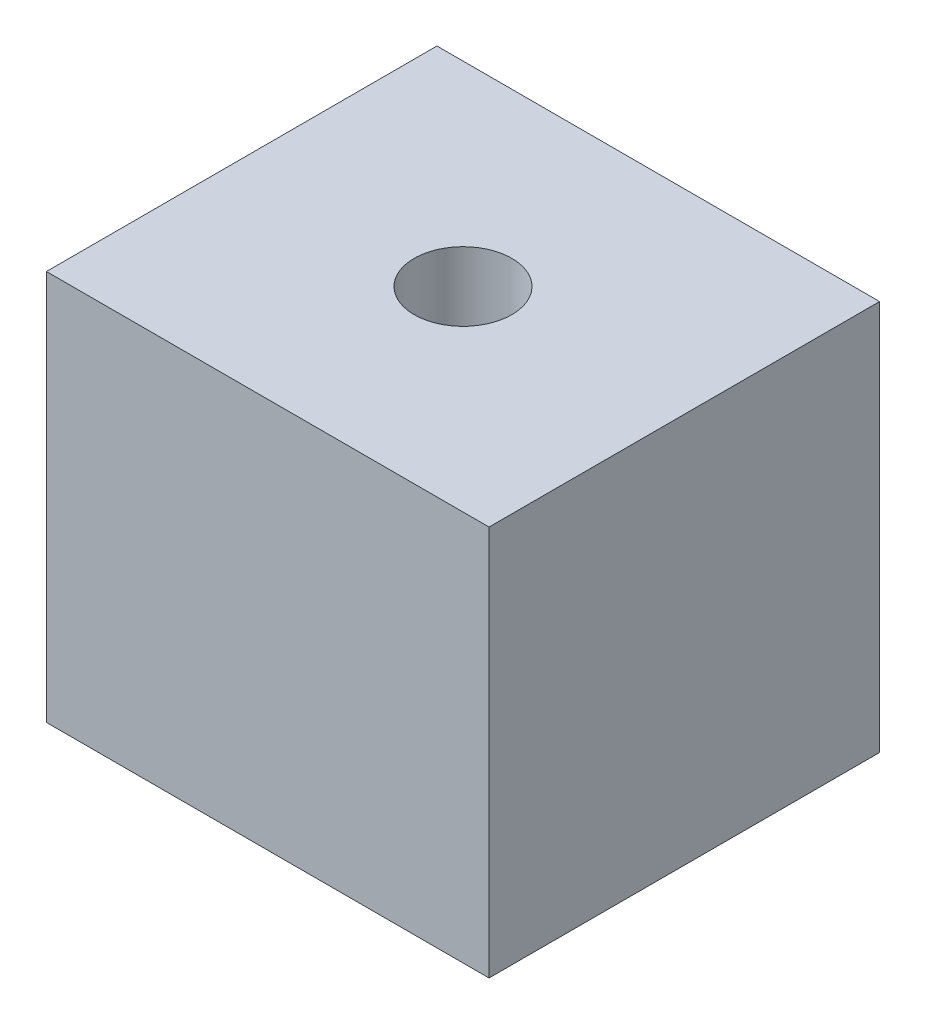
SolidWorks part; units mm, degrees
ref_plane "Front Plane" through (0, 0, 0) normal (0, 0, 1) x (1, 0, 0)
ref_plane "Top Plane" through (0, 0, 0) normal (0, 1, 0) x (1, 0, 0)
ref_plane "Right Plane" through (0, 0, 0) normal (1, 0, 0) x (0, 0, -1)
sketch "Sketch1" plane through (0, 0, 0) normal (0, 0, 1) x (1, 0, 0)
  line L1 (0, 0) -> (34, 0)
  line L2 (0, 0) -> (0, 30)
  line L3 (0, 30) -> (34, 30)
  line L4 (34, 0) -> (34, 30)
  circle A0 centre (4.75, 25.25) radius 2
  circle A1 centre (29.25, 25.25) radius 2
  circle A2 centre (29.25, 4.75) radius 2
  circle A3 centre (4.75, 4.75) radius 2
  dimension "D3" = 4
  dimension "D6" = 4
  dimension "D13" = 4
  dimension "D14" = 4
  dimension "D1" = 30
  dimension "D2" = 34
  dimension "D4" = 4.75
  dimension "D5" = 4.75
  dimension "D7" = 4.75
  dimension "D8" = 4.75
  dimension "D9" = 4.75
  dimension "D10" = 4.75
  dimension "D11" = 4.75
  dimension "D12" = 4.75
extrude "Boss-Extrude1" add sketch "Sketch1" along normal blind 30
sketch "Sketch2" plane through (0, 0, 30) normal (0, 0, 1) x (1, 0, 0)
  line L1 (0, 30) -> (34, 30)
  line L2 (0, 30) -> (0, 0)
  line L3 (0, 0) -> (34, 0)
  line L4 (34, 30) -> (34, 0)
extrude "Boss-Extrude2" add sketch "Sketch2" against normal blind 23
sketch "Sketch3" plane through (0, 30, 0) normal (0, 1, 0) x (1, 0, 0)
  line L0 (34, -30) -> (34, 0) construction
  line L1 (34, 0) -> (0, 0) construction
  circle A0 centre (17, -15) radius 3.75
  dimension "D1" = 17
  dimension "D3" = 7.5
  dimension "D2" = 15
extrude "Cut-Extrude1" cut sketch "Sketch3" against normal blind 30
